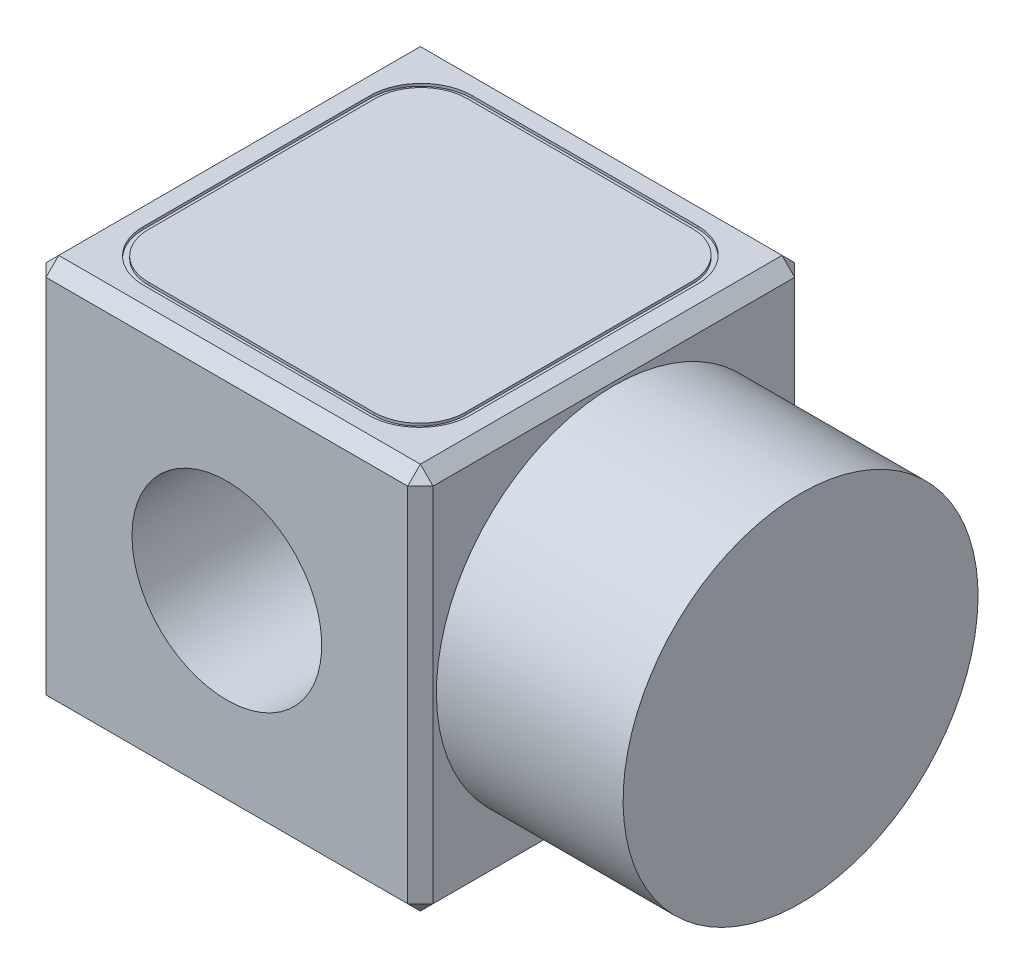
SolidWorks part; units mm, degrees
ref_plane "Front Plane" through (0, 0, 0) normal (0, 0, 1) x (1, 0, 0)
ref_plane "Top Plane" through (0, 0, 0) normal (0, 1, 0) x (1, 0, 0)
ref_plane "Right Plane" through (0, 0, 0) normal (1, 0, 0) x (0, 0, -1)
sketch "Sketch1" plane through (1848.7405, 0, 0) normal (-1, 0, 0) x (0, 0, 1)
  line L1 (-38.165, -38.165) -> (38.165, -38.165)
  line L2 (-38.165, -38.165) -> (-38.165, 38.165)
  line L3 (-38.165, 38.165) -> (38.165, 38.165)
  line L4 (38.165, -38.165) -> (38.165, 38.165)
  line L5 (-38.165, -38.165) -> (38.165, 38.165) construction
  line L6 (-38.165, 38.165) -> (38.165, -38.165) construction
  circle A0 centre (0, 0) radius 35 construction
  dimension "D1" = 70
  dimension "D2" = 76.33
  dimension "D3" = 76.33
extrude "Boss-Extrude1" add sketch "Sketch1" along normal blind 76.33 contours A0 | L2 L1 L4 L3
sketch "Sketch2" plane through (1848.7405, 0, 0) normal (1, 0, 0) x (0, 0, -1)
  circle A0 centre (0, 0) radius 35
  dimension "D1" = 70
extrude "Boss-Extrude2" add sketch "Sketch2" along normal blind 36.82
chamfer "Chamfer1" distance 2.5 angle 45 12 edges at (1848.7405, 0, -38.165) (1810.5755, 38.165, -38.165) (1848.7405, 38.165, 0) (1810.5755, 38.165, 38.165) (1848.7405, 0, 38.165) (1810.5755, -38.165, -38.165) (1848.7405, -38.165, 0) (1810.5755, -38.165, 38.165) (1772.4105, 0, 38.165) (1772.4105, -38.165, 0) (1772.4105, 0, -38.165) (1772.4105, 38.165, 0)
sketch "Sketch3" plane through (0, 0, -38.165) normal (0, 0, -1) x (-1, 0, 0)
  line L0 (-1810.5755, 35.665) -> (-1810.5755, -35.665) construction
  line L4 (-1774.9105, 35.665) -> (-1846.2405, 35.665)
  line L5 (-1846.2405, 35.665) -> (-1846.2405, -35.665)
  line L6 (-1846.2405, -35.665) -> (-1774.9105, -35.665)
  line L7 (-1774.9105, -35.665) -> (-1774.9105, 35.665)
  line L8 (-1774.9105, 35.665) -> (-1846.2405, 35.665)
  line L9 (-1846.2405, 35.665) -> (-1846.2405, -35.665)
  line L10 (-1846.2405, -35.665) -> (-1774.9105, -35.665)
  line L11 (-1774.9105, -35.665) -> (-1774.9105, 35.665)
  circle A0 centre (-1810.5755, 0) radius 18.71
  dimension "D2" = 37.42
  dimension "D1" = 0
extrude "Cut-Extrude1" cut sketch "Sketch3" against normal up to next contours A0 L0 | L0 A0
sketch "Sketch5" plane through (0, 38.165, 0) normal (0, 1, 0) x (1, 0, 0)
  line L0 (1696.0805, -38.1651) -> (1848.7405, -38.1651)
  line L1 (1772.4105, -38.1651) -> (1772.4105, 38.1649)
  line L2 (1848.7405, 38.1649) -> (1696.0805, 38.1649)
  line L3 (1696.0805, 38.1649) -> (1696.0805, -38.1651)
  line L4 (1712.0288, 31.8944) -> (1756.4621, 31.8944)
  line L5 (1765.9835, 22.373) -> (1765.9835, -22.3731)
  line L6 (1756.4621, -31.8946) -> (1712.0288, -31.8946)
  line L7 (1702.5074, -22.3731) -> (1702.5074, 22.373)
  line L8 (1707.4818, -16.2789) -> (1737.0443, 9.2048)
  line L9 (1709.8333, -19.3733) -> (1745.0124, -1.4545)
  line L10 (1737.0994, 9.2048) -> (1745.0124, -1.4545)
  line L11 (1734.2455, 38.1649) -> (1734.2455, -38.1651)
  line L12 (1696.0805, -0.0001) -> (1848.7405, -0.0001) construction
  line L13 (1711.0683, -23.425) -> (1757.4227, -23.425)
  line L14 (1757.4227, -23.425) -> (1757.4227, 23.4248)
  line L15 (1757.4227, 23.4248) -> (1711.0683, 23.4248)
  line L16 (1711.0683, 23.4248) -> (1711.0683, -23.425)
  line L17 (1833.7527, 23.4248) -> (1833.7527, -23.425) construction
  line L18 (1787.3983, 23.4248) -> (1833.7527, 23.4248) construction
  line L19 (1787.3983, -23.425) -> (1787.3983, 23.4248) construction
  line L20 (1833.7527, -23.425) -> (1787.3983, -23.425) construction
  line L21 (1810.5755, 38.1649) -> (1810.5755, -38.1651) construction
  line L22 (1807.7216, 9.2048) -> (1799.8086, -1.4545) construction
  line L23 (1834.9877, -19.3733) -> (1799.8086, -1.4545) construction
  line L24 (1837.3392, -16.2789) -> (1807.7767, 9.2048) construction
  line L25 (1842.3136, -22.3731) -> (1842.3136, 22.373) construction
  line L26 (1788.3589, -31.8946) -> (1832.7922, -31.8946)
  line L27 (1778.8375, 22.373) -> (1778.8375, -22.3731)
  line L28 (1832.7922, 31.8944) -> (1788.3589, 31.8944)
  line L29 (1848.7405, 38.1649) -> (1848.7405, -38.1651)
  line L30 (1846.2405, 0) -> (1774.9105, 0) construction
  line L31 (1846.2405, -35.665) -> (1846.2405, 35.665) construction
  line L32 (1774.9105, 35.665) -> (1774.9105, -35.665) construction
  line L33 (1788.3589, -32.3946) -> (1832.7922, -32.3946)
  line L34 (1842.8136, -22.3731) -> (1842.8136, 22.373)
  line L35 (1832.7922, 32.3944) -> (1788.3589, 32.3944)
  line L36 (1778.3375, 22.373) -> (1778.3375, -22.3731)
  line L37 (1788.3589, -31.3946) -> (1832.7922, -31.3946)
  line L38 (1841.8136, -22.3731) -> (1841.8136, 22.373)
  line L39 (1832.7922, 31.3944) -> (1788.3589, 31.3944)
  line L40 (1779.3375, 22.373) -> (1779.3375, -22.3731)
  ellipse E0 centre (1710.9972, 23.1061) end of major axis (1710.9972, 26.2134) minor radius 3.0944
  ellipse E1 centre (1757.5728, 23.1061) end of major axis (1757.5728, 26.2134) minor radius 3.0944
  ellipse E2 centre (1710.9972, -23.7436) end of major axis (1710.9972, -26.8509) minor radius 3.0944
  ellipse E3 centre (1757.5728, -23.7436) end of major axis (1757.5728, -26.8509) minor radius 3.0944
  ellipse E4 centre (1709.0453, -17.5448) end of major axis (1709.0453, -15.5529) minor radius 1.9836
  ellipse E5 centre (1734.2455, 0) end of major axis (1734.2455, -1.1951) minor radius 1.1902
  ellipse E6 centre (1810.5755, 0) end of major axis (1810.5755, 1.1951) minor radius 1.1902 construction
  ellipse E7 centre (1835.7757, -17.5448) end of major axis (1835.7757, -15.5529) minor radius 1.9836 construction
  ellipse E8 centre (1787.2482, -23.7436) end of major axis (1787.2482, -20.6363) minor radius 3.0944
  ellipse E9 centre (1833.8238, -23.7436) end of major axis (1833.8238, -20.6363) minor radius 3.0944
  ellipse E10 centre (1787.2482, 23.1061) end of major axis (1787.2482, 26.2134) minor radius 3.0944
  ellipse E11 centre (1833.8238, 23.1061) end of major axis (1833.8238, 26.2134) minor radius 3.0944
  spline S0 degree 3 poles (1756.4621, 31.8944) (1761.6989, 31.8944) (1765.9835, 27.6097) (1765.9835, 22.373) knots 0.111111 0.111111 0.111111 0.111111 0.222222 0.222222 0.222222 0.222222
  spline S1 degree 3 poles (1765.9835, -22.3731) (1765.9835, -27.61) (1761.6989, -31.8946) (1756.4621, -31.8946) knots 0.333333 0.333333 0.333333 0.333333 0.444444 0.444444 0.444444 0.444444
  spline S2 degree 3 poles (1712.0288, -31.8946) (1706.792, -31.8946) (1702.5074, -27.61) (1702.5074, -22.3731) knots 0.555556 0.555556 0.555556 0.555556 0.666667 0.666667 0.666667 0.666667
  spline S3 degree 3 poles (1702.5074, 22.373) (1702.5074, 27.6097) (1706.792, 31.8944) (1712.0288, 31.8944) knots 0.777778 0.777778 0.777778 0.777778 1 1 1 1
  spline S4 degree 3 poles (1842.3136, 22.373) (1842.3136, 27.6097) (1838.029, 31.8944) (1832.7922, 31.8944) knots 0.777778 0.777778 0.777778 0.777778 1 1 1 1
  spline S5 degree 3 poles (1832.7922, -31.8946) (1838.029, -31.8946) (1842.3136, -27.61) (1842.3136, -22.3731) knots 0.555556 0.555556 0.555556 0.555556 0.666667 0.666667 0.666667 0.666667
  spline S6 degree 3 poles (1778.8375, -22.3731) (1778.8375, -27.61) (1783.1221, -31.8946) (1788.3589, -31.8946) knots 0.333333 0.333333 0.333333 0.333333 0.444444 0.444444 0.444444 0.444444
  spline S7 degree 3 poles (1788.3589, 31.8944) (1783.1221, 31.8944) (1778.8375, 27.6097) (1778.8375, 22.373) knots 0.111111 0.111111 0.111111 0.111111 0.222222 0.222222 0.222222 0.222222
  spline S8 degree 1 poles (1832.7922, -32.3946) (1842.8136, -22.3731) knots 0 0 1 1 construction
  spline S9 degree 1 poles (1842.8136, 22.373) (1832.7922, 32.3944) knots 0 0 1 1 construction
  spline S10 degree 1 poles (1788.3589, 32.3944) (1778.3375, 22.373) knots 0 0 1 1 construction
  spline S11 degree 1 poles (1778.3375, -22.3731) (1788.3589, -32.3946) knots 0 0 1 1 construction
  spline S12 degree 3 poles (1832.7922, -32.3946) (1833.4669, -32.3946) (1834.8346, -32.2537) (1837.3393, -31.4622) (1840.0436, -29.6246) (1841.8812, -26.9203) (1842.6727, -24.4155) (1842.8136, -23.0477) (1842.8136, -22.3731) knots 0.555556 0.555556 0.555556 0.555556 0.569444 0.583333 0.611111 0.638889 0.652778 0.666667 0.666667 0.666667 0.666667
  spline S13 degree 3 poles (1842.8136, 22.373) (1842.8136, 23.0476) (1842.6727, 24.4154) (1841.8812, 26.9201) (1840.0436, 29.6244) (1837.3393, 31.4619) (1834.8346, 32.2535) (1833.4669, 32.3944) (1832.7922, 32.3944) knots 0.777778 0.777778 0.777778 0.777778 0.805556 0.833333 0.888889 0.944444 0.972222 1 1 1 1
  spline S14 degree 3 poles (1788.3589, 32.3944) (1787.6843, 32.3944) (1786.3165, 32.2535) (1783.8118, 31.4619) (1781.1075, 29.6244) (1779.27, 26.9201) (1778.4784, 24.4154) (1778.3375, 23.0476) (1778.3375, 22.373) knots 0.111111 0.111111 0.111111 0.111111 0.125 0.138889 0.166667 0.194444 0.208333 0.222222 0.222222 0.222222 0.222222
  spline S15 degree 3 poles (1778.3375, -22.3731) (1778.3375, -23.0477) (1778.4784, -24.4155) (1779.27, -26.9203) (1781.1075, -29.6246) (1783.8118, -31.4622) (1786.3165, -32.2537) (1787.6843, -32.3946) (1788.3589, -32.3946) knots 0.333333 0.333333 0.333333 0.333333 0.347222 0.361111 0.388889 0.416667 0.430556 0.444444 0.444444 0.444444 0.444444
  spline S16 degree 1 poles (1832.7922, -31.3946) (1841.8136, -22.3731) knots 0 0 1 1 construction
  spline S17 degree 1 poles (1841.8136, 22.373) (1832.7922, 31.3944) knots 0 0 1 1 construction
  spline S18 degree 1 poles (1788.3589, 31.3944) (1779.3375, 22.373) knots 0 0 1 1 construction
  spline S19 degree 1 poles (1779.3375, -22.3731) (1788.3589, -31.3946) knots 0 0 1 1 construction
  spline S20 degree 3 poles (1832.7922, -31.3946) (1833.3992, -31.3946) (1834.6304, -31.2678) (1836.8816, -30.5564) (1839.3196, -28.9006) (1840.9754, -26.4625) (1841.6868, -24.2113) (1841.8136, -22.9801) (1841.8136, -22.3731) knots 0.555556 0.555556 0.555556 0.555556 0.569444 0.583333 0.611111 0.638889 0.652778 0.666667 0.666667 0.666667 0.666667
  spline S21 degree 3 poles (1841.8136, 22.373) (1841.8136, 22.98) (1841.6868, 24.2111) (1840.9754, 26.4623) (1839.3196, 28.9004) (1836.8816, 30.5561) (1834.6304, 31.2676) (1833.3992, 31.3944) (1832.7922, 31.3944) knots 0.777778 0.777778 0.777778 0.777778 0.805556 0.833333 0.888889 0.944444 0.972222 1 1 1 1
  spline S22 degree 3 poles (1788.3589, 31.3944) (1787.7519, 31.3944) (1786.5208, 31.2676) (1784.2696, 30.5561) (1781.8315, 28.9004) (1780.1758, 26.4623) (1779.4643, 24.2111) (1779.3375, 22.98) (1779.3375, 22.373) knots 0.111111 0.111111 0.111111 0.111111 0.125 0.138889 0.166667 0.194444 0.208333 0.222222 0.222222 0.222222 0.222222
  spline S23 degree 3 poles (1779.3375, -22.3731) (1779.3375, -22.9801) (1779.4643, -24.2113) (1780.1758, -26.4625) (1781.8315, -28.9006) (1784.2696, -30.5564) (1786.5208, -31.2678) (1787.7519, -31.3946) (1788.3589, -31.3946) knots 0.333333 0.333333 0.333333 0.333333 0.347222 0.361111 0.388889 0.416667 0.430556 0.444444 0.444444 0.444444 0.444444
  point P110 (1772.4105, -0.0001)
  point P127 (1810.5755, 0)
  dimension "D1" = 0.5
  dimension "D2" = 0.5
extrude "Cut-Extrude2" cut sketch "Sketch5" against normal blind 0.5
sketch "Sketch6" plane through (0, 38.165, 0) normal (0, 1, 0) x (1, 0, 0)
  line L0 (1778.3375, 22.373) -> (1778.3375, -22.3731)
  line L1 (1788.3589, -32.3946) -> (1832.7922, -32.3946)
  line L2 (1842.8136, -22.3731) -> (1842.8136, 22.373)
  line L3 (1832.7922, 32.3944) -> (1788.3589, 32.3944)
  line L4 (1779.3375, 22.373) -> (1779.3375, -22.3731)
  line L5 (1788.3589, -31.3946) -> (1832.7922, -31.3946)
  line L6 (1841.8136, -22.3731) -> (1841.8136, 22.373)
  line L7 (1832.7922, 31.3944) -> (1788.3589, 31.3944)
  line L8 (1779.3375, 22.373) -> (1779.3375, -22.3731)
  line L9 (1788.3589, -31.3946) -> (1832.7922, -31.3946)
  line L10 (1841.8136, -22.3731) -> (1841.8136, 22.373)
  line L11 (1832.7922, 31.3944) -> (1788.3589, 31.3944)
  line L12 (1780.3375, 22.373) -> (1780.3375, -22.3731)
  line L13 (1788.3589, -30.3946) -> (1832.7922, -30.3946)
  line L14 (1840.8136, -22.3731) -> (1840.8136, 22.373)
  line L15 (1832.7922, 30.3944) -> (1788.3589, 30.3944)
  line L16 (1810.5756, -30.3946) -> (1810.5756, 30.3944)
  spline S0 degree 1 poles (1778.3375, -22.3731) (1788.3589, -32.3946) knots 0 0 1 1 construction
  spline S1 degree 1 poles (1832.7922, -32.3946) (1842.8136, -22.3731) knots 0 0 1 1 construction
  spline S2 degree 1 poles (1842.8136, 22.373) (1832.7922, 32.3944) knots 0 0 1 1 construction
  spline S3 degree 1 poles (1788.3589, 32.3944) (1778.3375, 22.373) knots 0 0 1 1 construction
  spline S4 degree 3 poles (2655.4468, -2888.8231) (1882.6743, 80.9152) (1771.7065, 0.3382) (1780.1758, -26.4625) (1781.8315, -28.9006) (1784.2696, -30.5564) (1811.0705, -39.0258) (1891.6457, 71.9479) (-1078.0213, 844.7495) knots -0.272493 -0.272493 -0.272493 -0.272493 0.347222 0.361111 0.388889 0.416667 0.430556 1.050286 1.050286 1.050286 1.050286 only from (1779.3375, -22.3731) to (1788.3589, -31.3946)
  spline S5 degree 3 poles (4699.242, 844.7676) (1729.5042, 71.9496) (1810.0804, -39.0259) (1836.8816, -30.5564) (1839.3196, -28.9006) (1840.9754, -26.4625) (1849.4446, 0.338) (1738.478, 80.9143) (965.7165, -2888.7761) knots -0.050291 -0.050291 -0.050291 -0.050291 0.569444 0.583333 0.611111 0.638889 0.652778 1.272489 1.272489 1.272489 1.272489 only from (1832.7922, -31.3946) to (1841.8136, -22.3731)
  spline S6 degree 3 poles (965.5285, 2888.7383) (1738.4582, -80.9141) (1849.4453, -0.34) (1840.9754, 26.4623) (1839.3196, 28.9004) (1836.8816, 30.5561) (1810.0804, 39.0258) (1729.5049, -71.9512) (4699.1815, -844.8328) knots -0.433981 -0.433981 -0.433981 -0.433981 0.805556 0.833333 0.888889 0.944444 0.972222 2.211694 2.211694 2.211694 2.211694 only from (1841.8136, 22.373) to (1832.7922, 31.3944)
  spline S7 degree 3 poles (-1078.0651, -844.8419) (1891.6469, -71.9521) (1811.0708, 39.0259) (1784.2696, 30.5561) (1781.8315, 28.9004) (1780.1758, 26.4623) (1771.7057, -0.3403) (1882.6953, -80.9158) (2655.6478, 2888.8351) knots -0.494738 -0.494738 -0.494738 -0.494738 0.125 0.138889 0.166667 0.194444 0.208333 0.828108 0.828108 0.828108 0.828108 only from (1788.3589, 31.3944) to (1779.3375, 22.373)
  spline S8 degree 3 poles (1779.3375, -22.3731) (1779.3375, -22.9801) (1779.4643, -24.2113) (1780.1758, -26.4625) (1781.8315, -28.9006) (1784.2696, -30.5564) (1786.5208, -31.2678) (1787.7519, -31.3946) (1788.3589, -31.3946) knots 0.333333 0.333333 0.333333 0.333333 0.347222 0.361111 0.388889 0.416667 0.430556 0.444444 0.444444 0.444444 0.444444
  spline S9 degree 3 poles (1832.7922, -31.3946) (1833.3992, -31.3946) (1834.6304, -31.2678) (1836.8816, -30.5564) (1839.3196, -28.9006) (1840.9754, -26.4625) (1841.6868, -24.2113) (1841.8136, -22.9801) (1841.8136, -22.3731) knots 0.555556 0.555556 0.555556 0.555556 0.569444 0.583333 0.611111 0.638889 0.652778 0.666667 0.666667 0.666667 0.666667
  spline S10 degree 3 poles (1841.8136, 22.373) (1841.8136, 22.98) (1841.6868, 24.2111) (1840.9754, 26.4623) (1839.3196, 28.9004) (1836.8816, 30.5561) (1834.6304, 31.2676) (1833.3992, 31.3944) (1832.7922, 31.3944) knots 0.777778 0.777778 0.777778 0.777778 0.805556 0.833333 0.888889 0.944444 0.972222 1 1 1 1
  spline S11 degree 3 poles (1788.3589, 31.3944) (1787.7519, 31.3944) (1786.5208, 31.2676) (1784.2696, 30.5561) (1781.8315, 28.9004) (1780.1758, 26.4623) (1779.4643, 24.2111) (1779.3375, 22.98) (1779.3375, 22.373) knots 0.111111 0.111111 0.111111 0.111111 0.125 0.138889 0.166667 0.194444 0.208333 0.222222 0.222222 0.222222 0.222222
  spline S12 degree 3 poles (1778.3375, -22.3731) (1778.3375, -23.0473) (1778.4779, -24.4133) (1779.2707, -26.9228) (1781.1081, -29.624) (1783.8093, -31.4614) (1786.3188, -32.2542) (1787.6847, -32.3946) (1788.3589, -32.3946) knots 0.333333 0.333333 0.333333 0.333333 0.347222 0.361111 0.388889 0.416667 0.430556 0.444444 0.444444 0.444444 0.444444
  spline S13 degree 3 poles (1832.7922, -32.3946) (1833.4665, -32.3946) (1834.8324, -32.2542) (1837.3419, -31.4614) (1840.043, -29.624) (1841.8804, -26.9228) (1842.6733, -24.4133) (1842.8136, -23.0473) (1842.8136, -22.3731) knots 0.555556 0.555556 0.555556 0.555556 0.569444 0.583333 0.611111 0.638889 0.652778 0.666667 0.666667 0.666667 0.666667
  spline S14 degree 3 poles (1842.8136, 22.373) (1842.8136, 23.0472) (1842.6733, 24.4131) (1841.8804, 26.9226) (1840.043, 29.6238) (1837.3419, 31.4612) (1834.8324, 32.254) (1833.4665, 32.3944) (1832.7922, 32.3944) knots 0.777778 0.777778 0.777778 0.777778 0.805556 0.833333 0.888889 0.944444 0.972222 1 1 1 1
  spline S15 degree 3 poles (1788.3589, 32.3944) (1787.6847, 32.3944) (1786.3188, 32.254) (1783.8093, 31.4612) (1781.1081, 29.6238) (1779.2707, 26.9226) (1778.4779, 24.4131) (1778.3375, 23.0472) (1778.3375, 22.373) knots 0.111111 0.111111 0.111111 0.111111 0.125 0.138889 0.166667 0.194444 0.208333 0.222222 0.222222 0.222222 0.222222
  spline S16 degree 1 poles (1780.3375, -22.3731) (1788.3589, -30.3946) knots 0 0 1 1 construction
  spline S17 degree 1 poles (1832.7922, -30.3946) (1840.8136, -22.3731) knots 0 0 1 1 construction
  spline S18 degree 1 poles (1840.8136, 22.373) (1832.7922, 30.3944) knots 0 0 1 1 construction
  spline S19 degree 1 poles (1788.3589, 30.3944) (1780.3375, 22.373) knots 0 0 1 1 construction
  spline S20 degree 3 poles (1780.3375, -22.3731) (1780.3375, -22.9129) (1780.4508, -24.0093) (1781.0808, -26.0022) (1782.5549, -28.1772) (1784.7299, -29.6513) (1786.7228, -30.2813) (1787.8191, -30.3946) (1788.3589, -30.3946) knots 0.333333 0.333333 0.333333 0.333333 0.347222 0.361111 0.388889 0.416667 0.430556 0.444444 0.444444 0.444444 0.444444
  spline S21 degree 3 poles (1832.7922, -30.3946) (1833.332, -30.3946) (1834.4284, -30.2813) (1836.4213, -29.6513) (1838.5962, -28.1772) (1840.0703, -26.0022) (1840.7003, -24.0093) (1840.8136, -22.9129) (1840.8136, -22.3731) knots 0.555556 0.555556 0.555556 0.555556 0.569444 0.583333 0.611111 0.638889 0.652778 0.666667 0.666667 0.666667 0.666667
  spline S22 degree 3 poles (1840.8136, 22.373) (1840.8136, 22.9128) (1840.7003, 24.0091) (1840.0703, 26.002) (1838.5962, 28.177) (1836.4213, 29.6511) (1834.4284, 30.2811) (1833.332, 30.3944) (1832.7922, 30.3944) knots 0.777778 0.777778 0.777778 0.777778 0.805556 0.833333 0.888889 0.944444 0.972222 1 1 1 1
  spline S23 degree 3 poles (1788.3589, 30.3944) (1787.8191, 30.3944) (1786.7228, 30.2811) (1784.7299, 29.6511) (1782.5549, 28.177) (1781.0808, 26.002) (1780.4508, 24.0091) (1780.3375, 22.9128) (1780.3375, 22.373) knots 0.111111 0.111111 0.111111 0.111111 0.125 0.138889 0.166667 0.194444 0.208333 0.222222 0.222222 0.222222 0.222222
  dimension "D1" = 0
  dimension "D2" = 1
  dimension "D3" = 1
